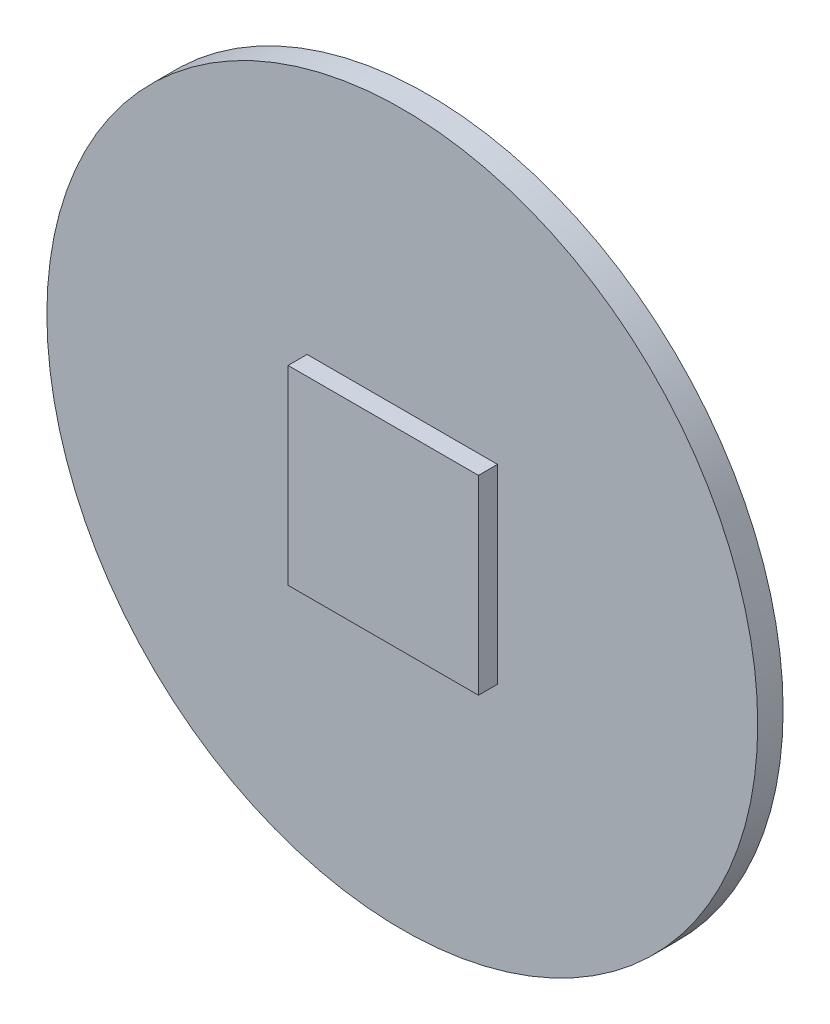
SolidWorks part; units mm, degrees
ref_plane "前视基准面" through (0, 0, 0) normal (0, 0, 1) x (1, 0, 0)
ref_plane "上视基准面" through (0, 0, 0) normal (0, 1, 0) x (1, 0, 0)
ref_plane "右视基准面" through (0, 0, 0) normal (1, 0, 0) x (0, 0, -1)
sketch "草图1" plane through (0, 0, 0) normal (0, 0, 1) x (1, 0, 0)
  circle A0 centre (0, 0) radius 28
  dimension "D1" = 56
extrude "凸台-拉伸1" add sketch "草图1" along normal blind 2
sketch "草图2" plane through (0, 0, 2) normal (0, 0, 1) x (1, 0, 0)
  line L1 (-7.5, -7.5) -> (7.5, -7.5)
  line L2 (-7.5, -7.5) -> (-7.5, 7.5)
  line L3 (-7.5, 7.5) -> (7.5, 7.5)
  line L4 (7.5, -7.5) -> (7.5, 7.5)
  line L5 (-7.5, -7.5) -> (7.5, 7.5) construction
  line L6 (-7.5, 7.5) -> (7.5, -7.5) construction
  point P0 (0, 0)
  dimension "D1" = 15
extrude "凸台-拉伸2" add sketch "草图2" along normal blind 1.5
sketch "草图4" plane through (0, 0, 0) normal (0, 0, -1) x (-1, 0, 0)
  line L1 (14, -10) -> (24, -10)
  line L2 (14, -10) -> (14, 10)
  line L3 (14, 10) -> (24, 10)
  line L4 (24, -10) -> (24, 10)
  line L5 (14, -10) -> (24, 10) construction
  line L6 (14, 10) -> (24, -10) construction
  point P0 (19, 0)
  dimension "D1" = 20
  dimension "D2" = 10
extrude "凸台-拉伸3" add sketch "草图4" along normal blind 1.5
sketch "草图5" plane through (0, 0, 0) normal (0, 0, -1) x (-1, 0, 0)
  line L1 (-7.5, -7.5) -> (7.5, -7.5)
  line L2 (-7.5, -7.5) -> (-7.5, 7.5)
  line L3 (-7.5, 7.5) -> (7.5, 7.5)
  line L4 (7.5, -7.5) -> (7.5, 7.5)
  line L5 (-7.5, -7.5) -> (7.5, 7.5) construction
  line L6 (-7.5, 7.5) -> (7.5, -7.5) construction
  point P0 (0, 0)
  dimension "D1" = 15
extrude "凸台-拉伸4" add sketch "草图5" along normal blind 1.5
